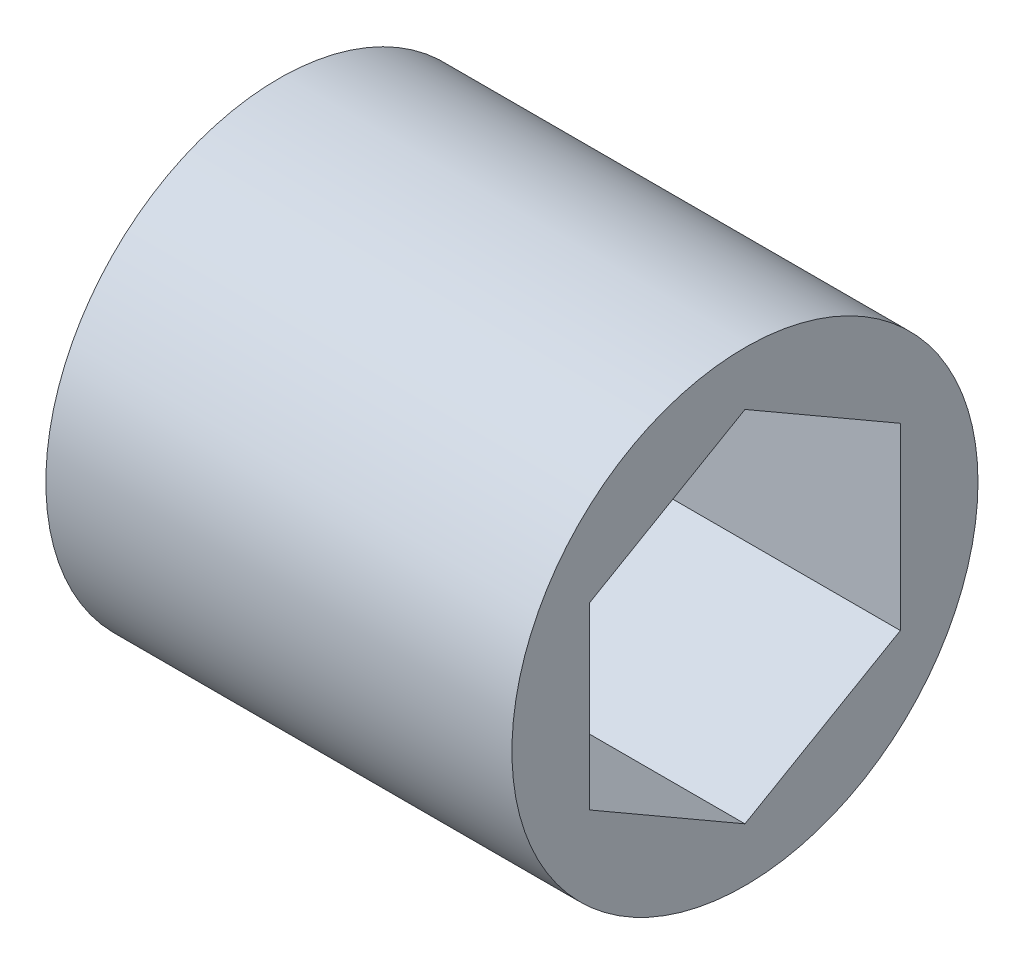
SolidWorks part; units mm, degrees
ref_plane "Front Plane" through (0, 0, 0) normal (0, 0, 1) x (1, 0, 0)
ref_plane "Top Plane" through (0, 0, 0) normal (0, 1, 0) x (1, 0, 0)
ref_plane "Right Plane" through (0, 0, 0) normal (1, 0, 0) x (0, 0, -1)
sketch "Bushing Profile" plane through (0, 0, 0) normal (1, 0, 0) x (0, 0, -1)
  line L1 (0, -4.8895) -> (4.2344, -2.4448)
  line L2 (4.2344, -2.4448) -> (4.2344, 2.4447)
  line L3 (4.2344, 2.4447) -> (0, 4.8895)
  line L4 (0, 4.8895) -> (-4.2344, 2.4448)
  line L5 (-4.2344, 2.4448) -> (-4.2344, -2.4448)
  line L6 (-4.2344, -2.4448) -> (0, -4.8895)
  circle A0 centre (0, 0) radius 4.8895 construction
  circle A1 centre (0, 0) radius 6.35
  dimension "D1" = 9.779
  dimension "D2" = 12.7
extrude "Bushing" add sketch "Bushing Profile" along normal blind 12.7
